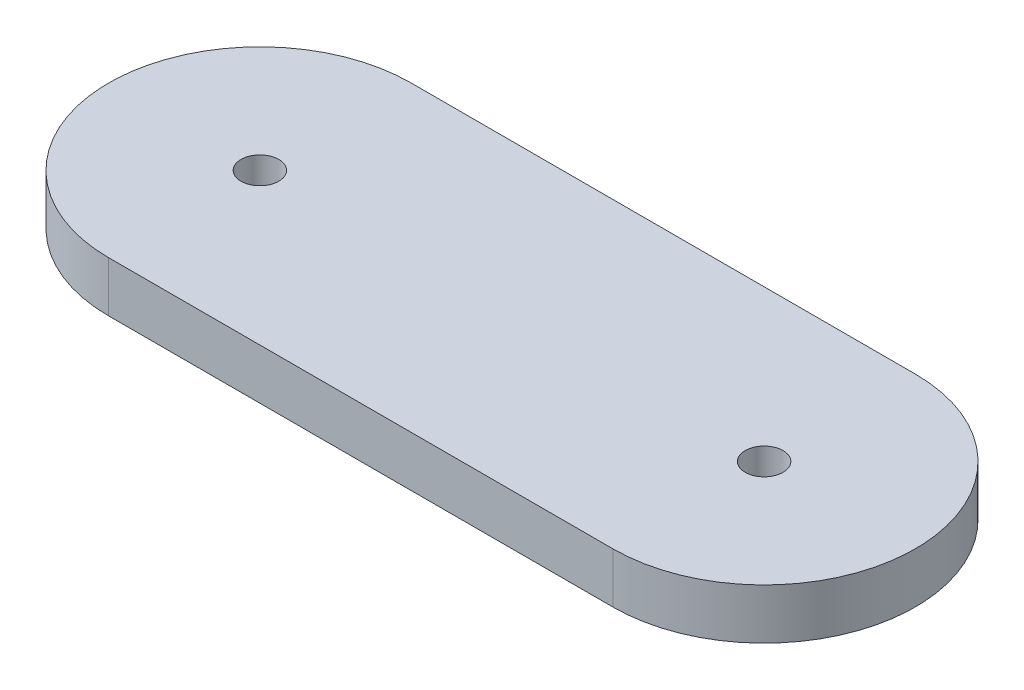
SolidWorks part; units mm, degrees
material "ASTM A36 Steel"
ref_plane "Front Plane" through (0, 0, 0) normal (0, 0, 1) x (1, 0, 0)
ref_plane "Top Plane" through (0, 0, 0) normal (0, 1, 0) x (1, 0, 0)
ref_plane "Right Plane" through (0, 0, 0) normal (1, 0, 0) x (0, 0, -1)
sketch "Sketch1" plane through (0, 0, 0) normal (0, 1, 0) x (1, 0, 0)
  line L1 (-66.9127, 38.1) -> (60.0873, 38.1)
  line L2 (-66.9127, 38.1) -> (-66.9127, -38.1)
  line L3 (-66.9127, -38.1) -> (60.0873, -38.1)
  line L4 (60.0873, 38.1) -> (60.0873, -38.1)
  circle A0 centre (-66.9127, 0) radius 38.1
  circle A1 centre (60.0873, 0) radius 38.1
  dimension "D1" = 76.2
  dimension "D2" = 76.2
  dimension "D3" = 127
extrude "Boss-Extrude1" add sketch "Sketch1" along normal blind 12.7 contours A0 | L2 L1 L4 L3 | A1
sketch "Sketch2" plane through (0, 12.7, 0) normal (0, 1, 0) x (1, 0, 0)
  circle A0 centre (-66.9127, 0) radius 4.7625
  circle A1 centre (60.0873, 0) radius 4.7625
  dimension "D1" = 9.525
  dimension "D2" = 9.525
extrude "Cut-Extrude2" cut sketch "Sketch2" against normal through all
